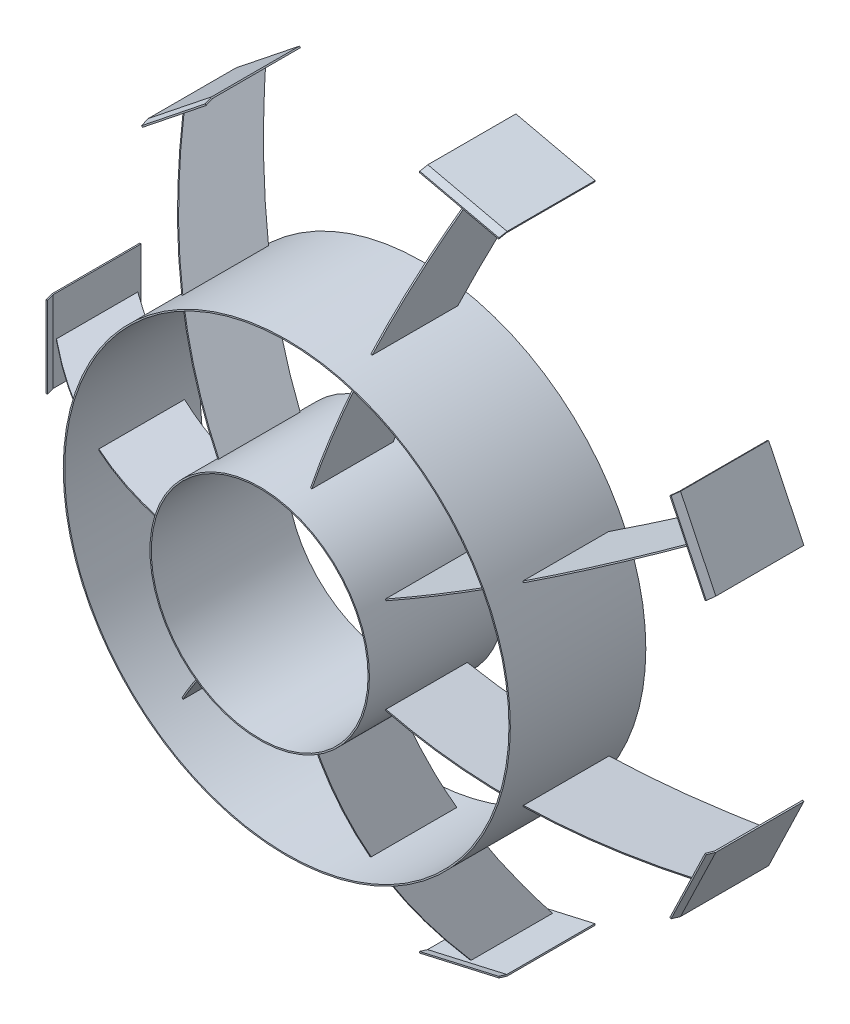
SolidWorks part; units mm, degrees
material "PF"
ref_plane "前视基准面" through (0, 0, 0) normal (0, 0, 1) x (1, 0, 0)
ref_plane "上视基准面" through (0, 0, 0) normal (0, 1, 0) x (1, 0, 0)
ref_plane "右视基准面" through (0, 0, 0) normal (1, 0, 0) x (0, 0, -1)
sketch "草图1" plane through (0, 0, 0) normal (0, 0, 1) x (1, 0, 0)
  circle A0 centre (0, 0) radius 16.5
  circle A1 centre (0, 0) radius 16.4
  dimension "D1" = 33
  dimension "D2" = 0.1
extrude "凸台-拉伸1" add sketch "草图1" along normal blind 10
ref_plane "基准面1" through (0, 0, 12) normal (0, 0, 1) x (1, 0, 0)
sketch "草图2" plane through (0, 0, 12) normal (0, 0, 1) x (1, 0, 0)
  circle A0 centre (0, 0) radius 8.1
  circle A1 centre (0, 0) radius 8
  dimension "D1" = 16
  dimension "D2" = 0.1
extrude "凸台-拉伸2" add sketch "草图2" against normal blind 10 separate body
sketch "草图3" plane through (0, 0, 0) normal (0, 1, 0) x (1, 0, 0)
  line L0 (-8.1, -2) -> (-8.1, -12) construction
  line L1 (-16.5, -10) -> (16.5, -10) construction
  line L2 (-25, 4) -> (-25, -2)
  line L3 (-8.1, -4) -> (-7.2368, -4)
  line L4 (-7.2368, -4) -> (-7.2368, -10)
  line L5 (-16.4, -10) -> (16.4, -10) construction
  line L6 (-7.2368, -10) -> (-8.1, -10)
  spline S0 degree 3 poles (-8.1, -10) (-14.9033, -8.8626) (-20.1618, -5.929) (-25, -2) knots 0 0 0 0 1 1 1 1
  spline S1 degree 3 poles (-8.1, -4) (-14.3871, -2.6373) (-19.9389, 0.3626) (-25, 4) knots 0 0 0 0 1 1 1 1
  point P0 (-8.1, -10)
  point P1 (-25, -2)
  point P6 (-8.1, -4)
  point P7 (-25, 4)
  dimension "D1" = 25
  dimension "D2" = 6
  dimension "D3" = 6
  dimension "D4" = 2
extrude "凸台-拉伸3" add sketch "草图3" along normal mid plane 0.1
sketch "草图4" plane through (0, 0, 12) normal (0, 0, 1) x (1, 0, 0)
  circle A0 centre (0, 0) radius 8
extrude "切除-拉伸1" cut sketch "草图4" against normal blind 500
pattern_circular "阵列(圆周)1" count 7 over 360 about axis through (0, 0, 10) along (0, 0, -1) of "凸台-拉伸3"
pattern_circular "阵列(圆周)2" count 7 over 360 about axis through (0, 0, 10) along (0, 0, -1) of "切除-拉伸1"
ref_plane "基准面2" through (0, 0, 2) normal (0, 0, 1) x (1, 0, 0)
sketch "草图7" plane through (22.5242, -10.8471, 0) normal (0.901, -0.4339, 0) x (0, 0, -1)
  line L0 (4, 0) -> (-15.5415, 0) construction
  line L1 (4, -0.05) -> (4, 0.05) construction
  line L2 (1, 0.05) -> (1, -2.0487) construction
  line L3 (4, 0.05) -> (-2, 0.05) construction
  line L5 (-2.25, 3) -> (4.25, 3)
  line L6 (-2.25, 3) -> (-2.25, -3)
  line L7 (-2.25, -3) -> (4.25, -3)
  line L8 (4.25, 3) -> (4.25, -3)
  line L9 (-2.25, 3) -> (4.25, -3) construction
  line L10 (-2.25, -3) -> (4.25, 3) construction
  point P9 (1, 0)
  point P11 (1, 0)
  dimension "D1" = 6
  dimension "D2" = 6.5
extrude "凸台-拉伸6" add sketch "草图7" along normal blind 0.1
sketch "草图8" plane through (-1.3017, -2.7029, 0) normal (-0.4339, -0.901, 0) x (0.901, -0.4339, 0)
  line L0 (25, 2.25) -> (24.8486, 2.8151)
  line L1 (25.1, 2.25) -> (24.9486, 2.8151)
  line L2 (24.8486, 2.8151) -> (24.9486, 2.8151)
  line L3 (25, 2.25) -> (25.1, 2.25)
  line L4 (25.1, 2.25) -> (25.1, -4.25) construction
  dimension "D1" = 0.1
  dimension "D2" = 165
extrude "凸台-拉伸7" add sketch "草图8" against normal blind 6
pattern_circular "阵列(圆周)4" count 7 over 360 about axis through (0, 0, 0) along (0, 0, 1) of "凸台-拉伸7", "凸台-拉伸6"
